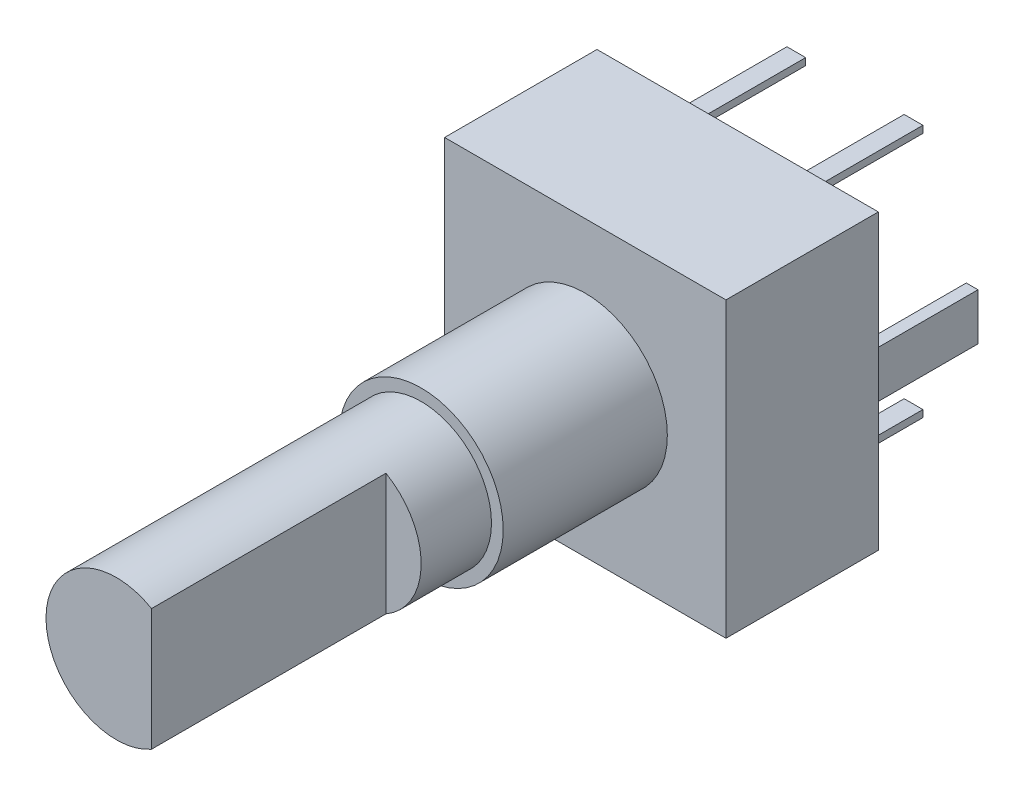
SolidWorks part; units mm, degrees
ref_plane "Front Plane" through (0, 0, 0) normal (0, 0, 1) x (1, 0, 0)
ref_plane "Top Plane" through (0, 0, 0) normal (0, 1, 0) x (1, 0, 0)
ref_plane "Right Plane" through (0, 0, 0) normal (1, 0, 0) x (0, 0, -1)
sketch "Sketch1" plane through (0, 0, 0) normal (0, 0, 1) x (1, 0, 0)
  line L1 (-6, -6.25) -> (6, -6.25)
  line L2 (-6, -6.25) -> (-6, 6.25)
  line L3 (-6, 6.25) -> (6, 6.25)
  line L4 (6, -6.25) -> (6, 6.25)
extrude "Body" add sketch "Sketch1" along normal blind 6.5
ref_plane "Plane_z6_5" through (0, 0, 6.5) normal (0, 0, 1) x (1, 0, 0)
sketch "Sketch2" plane through (0, 0, 6.5) normal (0, 0, 1) x (1, 0, 0)
  circle A0 centre (0, 0) radius 3.5
extrude "Bushing" add sketch "Sketch2" along normal blind 7
ref_plane "Plane_z13_5" through (0, 0, 13.5) normal (0, 0, 1) x (1, 0, 0)
sketch "Sketch3" plane through (0, 0, 13.5) normal (0, 0, 1) x (1, 0, 0)
  circle A0 centre (0, 0) radius 3
extrude "Shaft" add sketch "Sketch3" along normal blind 13
sketch "Sketch4" plane through (0, 0, 0) normal (0, 0, 1) x (1, 0, 0)
  line L1 (-2.9, -5.4) -> (-2.1, -5.4)
  line L2 (-2.9, -5.4) -> (-2.9, -5.1)
  line L3 (-2.9, -5.1) -> (-2.1, -5.1)
  line L4 (-2.1, -5.4) -> (-2.1, -5.1)
  line L6 (-0.4, -5.4) -> (0.4, -5.4)
  line L7 (-0.4, -5.4) -> (-0.4, -5.1)
  line L8 (-0.4, -5.1) -> (0.4, -5.1)
  line L9 (0.4, -5.4) -> (0.4, -5.1)
  line L11 (2.1, -5.4) -> (2.9, -5.4)
  line L12 (2.1, -5.4) -> (2.1, -5.1)
  line L13 (2.1, -5.1) -> (2.9, -5.1)
  line L14 (2.9, -5.4) -> (2.9, -5.1)
  line L16 (-2.9, 5.1) -> (-2.1, 5.1)
  line L17 (-2.9, 5.1) -> (-2.9, 5.4)
  line L18 (-2.9, 5.4) -> (-2.1, 5.4)
  line L19 (-2.1, 5.1) -> (-2.1, 5.4)
  line L21 (2.1, 5.1) -> (2.9, 5.1)
  line L22 (2.1, 5.1) -> (2.1, 5.4)
  line L23 (2.1, 5.4) -> (2.9, 5.4)
  line L24 (2.9, 5.1) -> (2.9, 5.4)
extrude "Pins" add sketch "Sketch4" against normal blind 5
sketch "Sketch5" plane through (0, 0, 0) normal (0, 0, 1) x (1, 0, 0)
  line L1 (-5.75, -1) -> (-5.25, -1)
  line L2 (-5.75, -1) -> (-5.75, 1)
  line L3 (-5.75, 1) -> (-5.25, 1)
  line L4 (-5.25, -1) -> (-5.25, 1)
  line L6 (5.25, -1) -> (5.75, -1)
  line L7 (5.25, -1) -> (5.25, 1)
  line L8 (5.25, 1) -> (5.75, 1)
  line L9 (5.75, -1) -> (5.75, 1)
extrude "Tabs" add sketch "Sketch5" against normal blind 4.5
ref_plane "Plane_z26_5" through (0, 0, 26.5) normal (0, 0, 1) x (1, 0, 0)
sketch "Sketch6" plane through (0, 0, 26.5) normal (0, 0, 1) x (1, 0, 0)
  line L1 (1.5, -4) -> (5.5, -4)
  line L2 (1.5, -4) -> (1.5, 4)
  line L3 (1.5, 4) -> (5.5, 4)
  line L4 (5.5, -4) -> (5.5, 4)
extrude "D_flat" cut sketch "Sketch6" against normal blind 10
